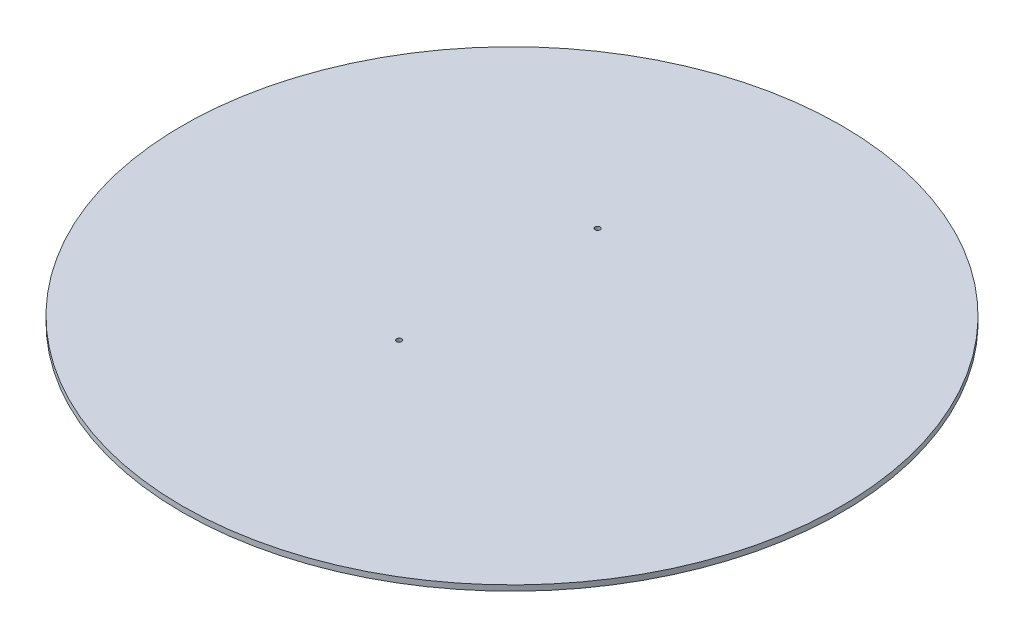
SolidWorks part; units mm, degrees
material "AISI 1020"
ref_plane "Front Plane" through (0, 0, 0) normal (0, 0, 1) x (1, 0, 0)
ref_plane "Top Plane" through (0, 0, 0) normal (0, 1, 0) x (1, 0, 0)
ref_plane "Right Plane" through (0, 0, 0) normal (1, 0, 0) x (0, 0, -1)
sketch "Sketch2" plane through (0, 0, 0) normal (0, 1, 0) x (1, 0, 0)
  circle A0 centre (0, 0) radius 304.8
  dimension "D1" = 609.6
extrude "Boss-Extrude1" add sketch "Sketch2" along normal blind 5.08
extrude "Cut-Extrude1" cut sketch "Sketch3" against normal through all
sketch "Sketch3" plane through (-66.634, 80.0246, -93.1741) normal (0.1079, 0.9936, 0.0319) x (0.9942, -0.108, -0.0006)
  circle A0 centre (41.7212, -167.1203) radius 2.3495
  circle A1 centre (44.0495, 14.2195) radius 2.3495
